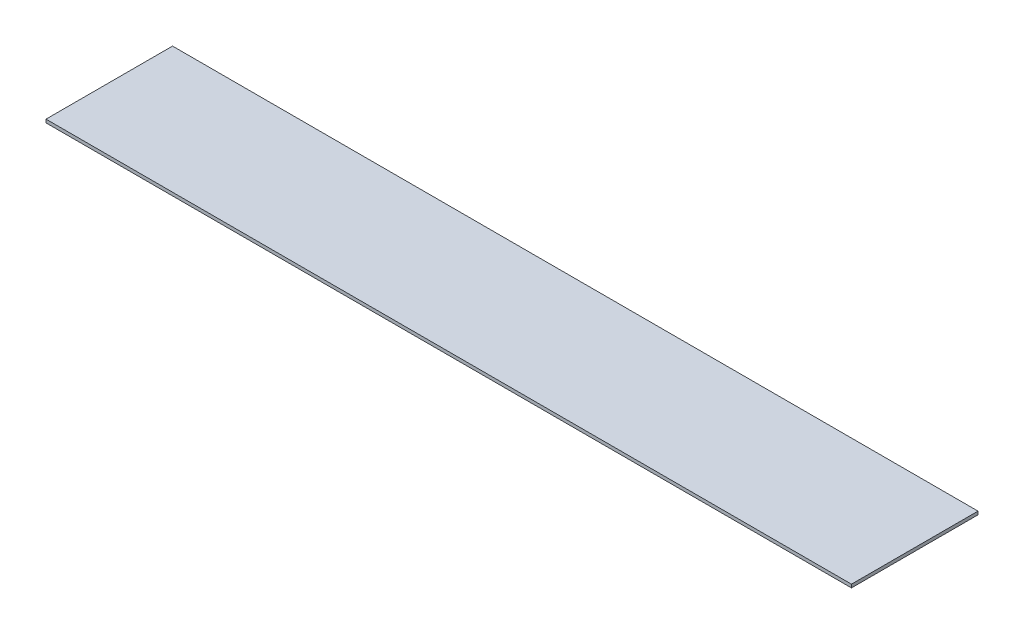
SolidWorks part; units mm, degrees
ref_plane "Front Plane" through (0, 0, 0) normal (0, 0, 1) x (1, 0, 0)
ref_plane "Top Plane" through (0, 0, 0) normal (0, 1, 0) x (1, 0, 0)
ref_plane "Right Plane" through (0, 0, 0) normal (1, 0, 0) x (0, 0, -1)
sketch "Sketch1" plane through (0, 0, 0) normal (0, 1, 0) x (1, 0, 0)
  line L1 (-59.1289, 156.3918) -> (1117.1451, 156.3918)
  line L2 (-59.1289, 156.3918) -> (-59.1289, -28.4005)
  line L3 (-59.1289, -28.4005) -> (1117.1451, -28.4005)
  line L4 (1117.1451, 156.3918) -> (1117.1451, -28.4005)
  dimension "D1" = 1176.274
  dimension "D2" = 184.7924
extrude "Boss-Extrude2" add sketch "Sketch1" along normal blind 4.7625
